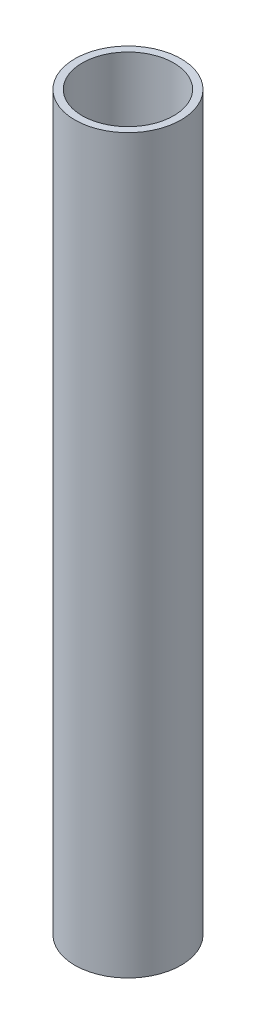
SolidWorks part; units mm, degrees
material "Thornel Mat VMA"
ref_plane "Front Plane" through (0, 0, 0) normal (0, 0, 1) x (1, 0, 0)
ref_plane "Top Plane" through (0, 0, 0) normal (0, 1, 0) x (1, 0, 0)
ref_plane "Right Plane" through (0, 0, 0) normal (1, 0, 0) x (0, 0, -1)
sketch "Sketch2" plane through (0, 0, 0) normal (0, 1, 0) x (1, 0, 0)
  circle A0 centre (0, 0) radius 7.366
  circle A1 centre (0, 0) radius 6.35
  dimension "D1" = 12.7
  dimension "D2" = 1.016
extrude "Boss-Extrude1" add sketch "Sketch2" along normal blind 101.6
